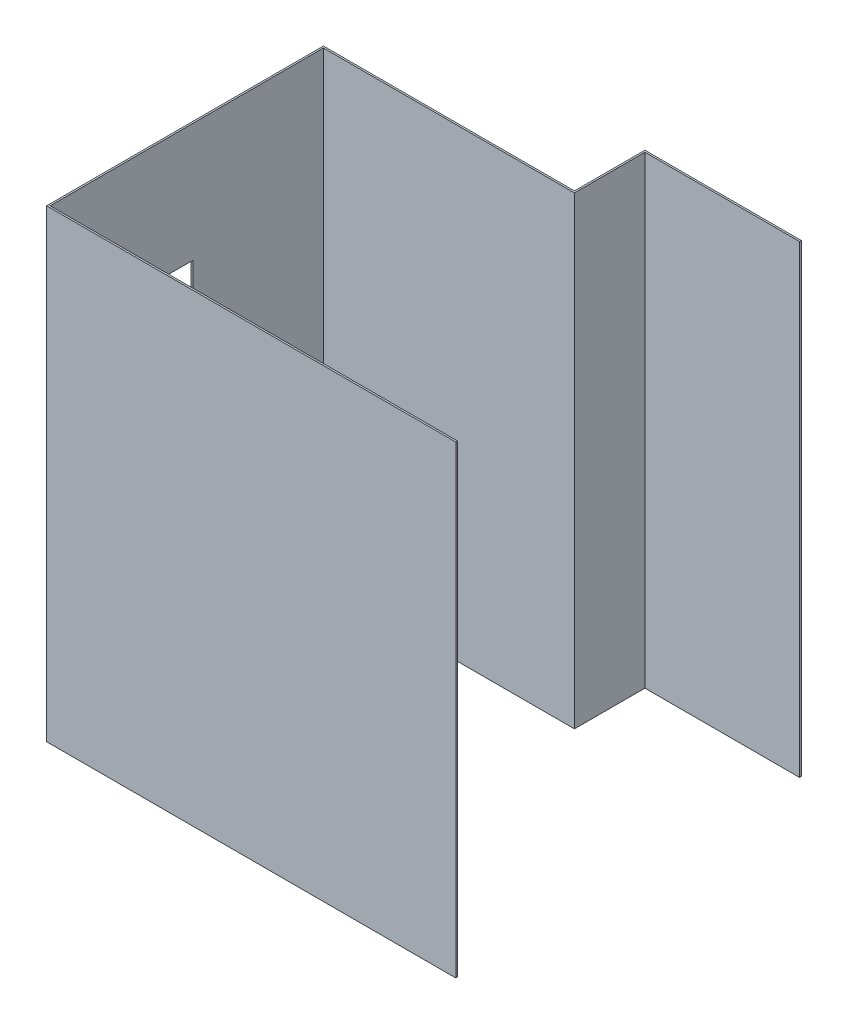
SolidWorks part; units mm, degrees
ref_plane "Front Plane" through (0, 0, 0) normal (0, 0, 1) x (1, 0, 0)
ref_plane "Top Plane" through (0, 0, 0) normal (0, 1, 0) x (1, 0, 0)
ref_plane "Right Plane" through (0, 0, 0) normal (1, 0, 0) x (0, 0, -1)
sketch "Sketch1" plane through (0, 0, 0) normal (0, 0, 1) x (1, 0, 0)
  line L1 (-730, 1350) -> (730, 1350)
  line L2 (-730, 1350) -> (-730, -1350)
  line L3 (-730, -1350) -> (730, -1350)
  line L4 (730, 1350) -> (730, -1350)
  line L5 (-730, 1350) -> (730, -1350) construction
  line L6 (-730, -1350) -> (730, 1350) construction
  point P0 (0, 0)
  dimension "D1" = 1460
  dimension "D2" = 2700
extrude "Boss-Extrude1" add sketch "Sketch1" along normal blind 10
sketch "Sketch2" plane through (730, 0, 0) normal (1, 0, 0) x (0, 0, -1)
  line L0 (-10, 1350) -> (400, 1350)
  line L1 (400, 1350) -> (400, -1350)
  line L2 (-10, -1350) -> (400, -1350)
  line L3 (-10, -1350) -> (-10, 1350)
  dimension "D1" = 410
extrude "Boss-Extrude2" add sketch "Sketch2" against normal blind 10
sketch "Sketch3" plane through (0, 0, -400) normal (0, 0, -1) x (-1, 0, 0)
  line L0 (-720, 1350) -> (-1630, 1350)
  line L1 (-720, 1350) -> (-720, -1350)
  line L2 (-720, -1350) -> (-1630, -1350)
  line L3 (-1630, -1350) -> (-1630, 1350)
  line L4 (-730, 1350) -> (-730, 51350) construction
  dimension "D1" = 900
extrude "Boss-Extrude3" add sketch "Sketch3" along normal blind 10
sketch "Sketch4" plane through (-730, 0, 0) normal (-1, 0, 0) x (0, 0, 1)
  line L0 (0, 1350) -> (1600, 1350)
  line L1 (1600, 1350) -> (1600, -1350)
  line L2 (1600, -1350) -> (0, -1350)
  line L3 (0, -1350) -> (0, 1350)
  line L4 (10, 1350) -> (10, -48650) construction
  dimension "D1" = 1590
extrude "Boss-Extrude4" add sketch "Sketch4" along normal blind 10
sketch "Sketch5" plane through (0, 0, 1600) normal (0, 0, 1) x (1, 0, 0)
  line L0 (-740, 1350) -> (1640, 1350)
  line L1 (730, 1350) -> (-730, 1350) construction
  line L2 (1640, 1350) -> (1640, -1350)
  line L3 (-730, -1350) -> (730, -1350) construction
  line L4 (1640, -1350) -> (-740, -1350)
  line L5 (-740, -1350) -> (-740, 1350)
  line L6 (-730, 1328.5706) -> (-730, 51328.5706) construction
  line L8 (-730, -1350) -> (-730, 1350) construction
  dimension "D1" = 2370
extrude "Boss-Extrude5" add sketch "Sketch5" along normal blind 10
sketch "Sketch6" plane through (-730, 0, 0) normal (1, 0, 0) x (0, 0, -1)
  line L0 (-1350, -1350) -> (-1350, 660)
  line L1 (-10, -1350) -> (-1600, -1350) construction
  line L2 (-1350, 660) -> (-770, 660)
  line L3 (-770, 660) -> (-770, -1350)
  line L4 (-770, -1350) -> (-1350, -1350)
  line L5 (-1600, -1350) -> (-1600, 1350) construction
  dimension "D1" = 250
  dimension "D2" = 580
  dimension "D3" = 2010
extrude "Cut-Extrude1" cut sketch "Sketch6" against normal up to next
